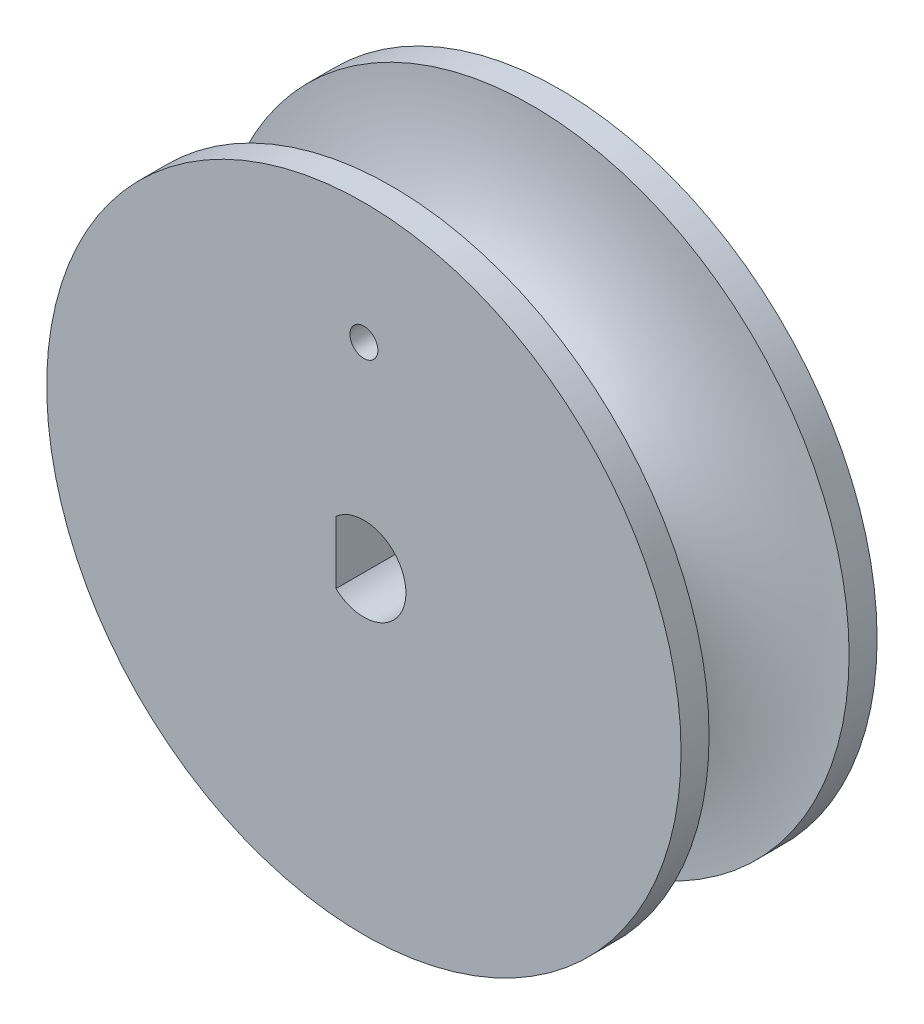
SolidWorks part; units mm, degrees
ref_plane "Front Plane" through (0, 0, 0) normal (0, 0, 1) x (1, 0, 0)
ref_plane "Top Plane" through (0, 0, 0) normal (0, 1, 0) x (1, 0, 0)
ref_plane "Right Plane" through (0, 0, 0) normal (1, 0, 0) x (0, 0, -1)
sketch "Sketch4" plane through (0, 0, 0) normal (1, 0, 0) x (0, 0, -1)
  line L0 (0, 0) -> (10.7579, 0) construction
  line L1 (-3.5, 11.325) -> (3.5, 11.325)
  line L2 (-3.5, 11.325) -> (-3.5, 1.5)
  line L3 (-3.5, 1.5) -> (3.5, 1.5)
  line L4 (3.5, 11.325) -> (3.5, 1.5)
  ellipse E0 centre (0, 11.325) end of major axis (0, 16.8852) minor radius 2.5
  dimension "D5" = 1
  dimension "D1" = 1.5
  dimension "D2" = 7
  dimension "D3" = 9.825
  dimension "D4" = 3.5
  dimension "D7" = 5.5602
revolve "Revolve1" add sketch "Sketch4" angle 360 about L0
sketch "Sketch7" plane through (0, 0, 3.5) normal (0, 0, 1) x (1, 0, 0)
  line L0 (-1, 1.118) -> (-1, -1.118)
  circle A0 centre (0, 0) radius 1.5 construction
  arc A1 (-1, -1.118) -> (-1, 1.118) centre (0, 0) cw
  point P5 (-1, 0)
  point P7 (-1.5, 0)
  dimension "D1" = 0.5
extrude "Boss-Extrude1" add sketch "Sketch7" against normal blind 7
sketch "Sketch8" plane through (0, 0, 3.5) normal (0, 0, 1) x (1, 0, 0)
  circle A0 centre (0, 7) radius 0.5
  dimension "D1" = 1
  dimension "D2" = 7
extrude "Cut-Extrude1" cut sketch "Sketch8" against normal blind 3
